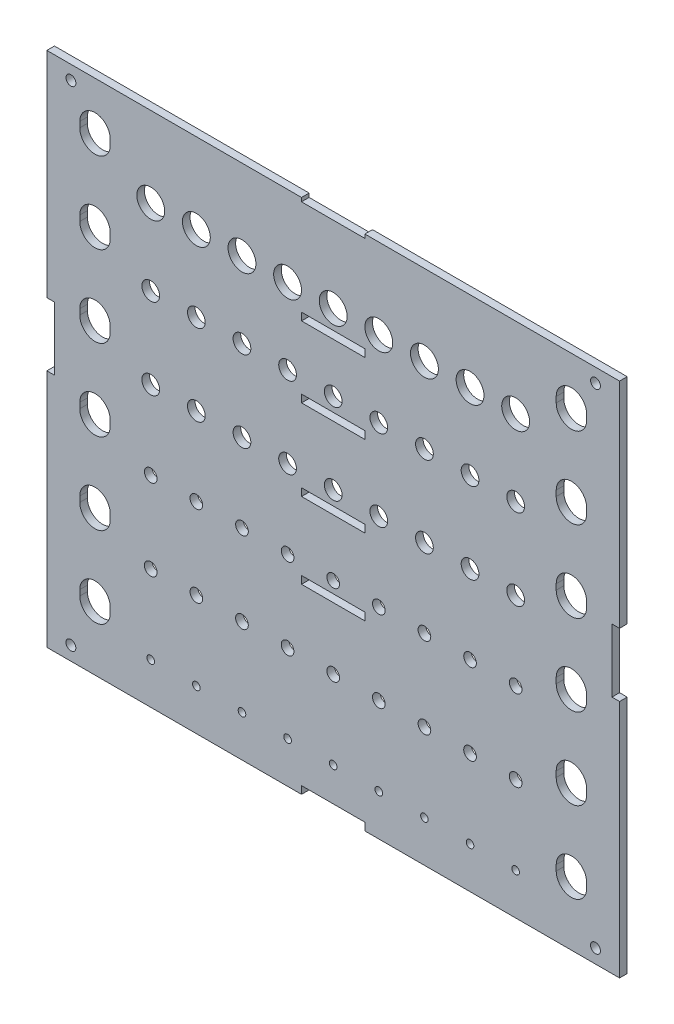
SolidWorks part; units mm, degrees
ref_plane "Спереди" through (0, 0, 0) normal (0, 0, 1) x (1, 0, 0)
ref_plane "Сверху" through (0, 0, 0) normal (0, 1, 0) x (1, 0, 0)
ref_plane "Справа" through (0, 0, 0) normal (1, 0, 0) x (0, 0, -1)
sketch "Эскиз1" plane through (0, 0, 0) normal (0, 0, 1) x (1, 0, 0)
  line L0 (98.0964, 112.1886) -> (98.0964, -117.8114)
  line L1 (-131.9036, 112.1886) -> (98.0964, 112.1886)
  line L2 (-131.9036, 112.1886) -> (-131.9036, -117.8114)
  line L3 (-131.9036, -117.8114) -> (98.0964, -117.8114)
  line L5 (-110.9036, 81.4289) -> (-110.9036, 79.2289) construction
  line L6 (77.0964, 81.4289) -> (77.0964, 79.2289) construction
  line L7 (83.0964, 81.4289) -> (83.0964, 79.2289)
  line L8 (71.0964, 81.4289) -> (71.0964, 79.2289)
  line L9 (-104.9036, 81.4289) -> (-104.9036, 79.2289)
  line L10 (83.0964, 49.4289) -> (83.0964, 47.2289)
  line L11 (71.0964, 49.4289) -> (71.0964, 47.2289)
  line L12 (-110.9036, 49.4289) -> (-110.9036, 47.2289) construction
  line L13 (-104.9036, 49.4289) -> (-104.9036, 47.2289)
  line L14 (-116.9036, 49.4289) -> (-116.9036, 47.2289)
  line L15 (77.0964, 49.4289) -> (77.0964, 47.2289) construction
  line L16 (83.0964, 17.4289) -> (83.0964, 15.2289)
  line L17 (71.0964, 17.4289) -> (71.0964, 15.2289)
  line L18 (-110.9036, 17.4289) -> (-110.9036, 15.2289) construction
  line L19 (-104.9036, 17.4289) -> (-104.9036, 15.2289)
  line L20 (-116.9036, 17.4289) -> (-116.9036, 15.2289)
  line L21 (77.0964, 17.4289) -> (77.0964, 15.2289) construction
  line L22 (83.0964, -14.5711) -> (83.0964, -16.7711)
  line L23 (71.0964, -14.5711) -> (71.0964, -16.7711)
  line L24 (-110.9036, -14.5711) -> (-110.9036, -16.7711) construction
  line L25 (-104.9036, -14.5711) -> (-104.9036, -16.7711)
  line L26 (-116.9036, -14.5711) -> (-116.9036, -16.7711)
  line L27 (77.0964, -14.5711) -> (77.0964, -16.7711) construction
  line L28 (83.0964, -46.5711) -> (83.0964, -48.7711)
  line L29 (71.0964, -46.5711) -> (71.0964, -48.7711)
  line L30 (-110.9036, -46.5711) -> (-110.9036, -48.7711) construction
  line L31 (-104.9036, -46.5711) -> (-104.9036, -48.7711)
  line L32 (-116.9036, 81.4289) -> (-116.9036, 79.2289)
  line L33 (-116.9036, -46.5711) -> (-116.9036, -48.7711)
  line L34 (77.0964, -46.5711) -> (77.0964, -48.7711) construction
  line L35 (83.0964, -78.5711) -> (83.0964, -80.7711)
  line L36 (71.0964, -78.5711) -> (71.0964, -80.7711)
  line L37 (-110.9036, -78.5711) -> (-110.9036, -80.7711) construction
  line L38 (-104.9036, -78.5711) -> (-104.9036, -80.7711)
  line L39 (-116.9036, -78.5711) -> (-116.9036, -80.7711)
  line L40 (77.0964, -78.5711) -> (77.0964, -80.7711) construction
  circle A2 centre (-120.4036, 93.6886) radius 1.95
  circle A3 centre (86.5964, 93.6886) radius 1.95
  circle A4 centre (86.5964, -99.3114) radius 1.95
  circle A5 centre (-120.4036, -99.3114) radius 1.95
  circle A71 centre (-88.9036, 67.4886) radius 5.5
  circle A73 centre (-88.9036, 5.4886) radius 3.5
  circle A75 centre (-88.9036, -57.5114) radius 2.5
  circle A76 centre (-88.9036, -88.5114) radius 1.5
  arc A117 (83.0964, 81.4289) -> (71.0964, 81.4289) centre (77.0964, 81.4289) ccw
  arc A118 (71.0964, 79.2289) -> (83.0964, 79.2289) centre (77.0964, 79.2289) ccw
  arc A119 (71.0964, 47.2289) -> (83.0964, 47.2289) centre (77.0964, 47.2289) ccw
  arc A120 (83.0964, 49.4289) -> (71.0964, 49.4289) centre (77.0964, 49.4289) ccw
  arc A121 (-104.9036, 49.4289) -> (-116.9036, 49.4289) centre (-110.9036, 49.4289) ccw
  arc A122 (-116.9036, 47.2289) -> (-104.9036, 47.2289) centre (-110.9036, 47.2289) ccw
  arc A123 (71.0964, 15.2289) -> (83.0964, 15.2289) centre (77.0964, 15.2289) ccw
  arc A124 (83.0964, 17.4289) -> (71.0964, 17.4289) centre (77.0964, 17.4289) ccw
  arc A125 (-104.9036, 17.4289) -> (-116.9036, 17.4289) centre (-110.9036, 17.4289) ccw
  arc A126 (-116.9036, 15.2289) -> (-104.9036, 15.2289) centre (-110.9036, 15.2289) ccw
  arc A127 (71.0964, -16.7711) -> (83.0964, -16.7711) centre (77.0964, -16.7711) ccw
  arc A128 (83.0964, -14.5711) -> (71.0964, -14.5711) centre (77.0964, -14.5711) ccw
  arc A129 (-104.9036, -14.5711) -> (-116.9036, -14.5711) centre (-110.9036, -14.5711) ccw
  arc A130 (-116.9036, -16.7711) -> (-104.9036, -16.7711) centre (-110.9036, -16.7711) ccw
  arc A131 (71.0964, -48.7711) -> (83.0964, -48.7711) centre (77.0964, -48.7711) ccw
  arc A132 (83.0964, -46.5711) -> (71.0964, -46.5711) centre (77.0964, -46.5711) ccw
  arc A133 (-104.9036, -46.5711) -> (-116.9036, -46.5711) centre (-110.9036, -46.5711) ccw
  arc A134 (-116.9036, -48.7711) -> (-104.9036, -48.7711) centre (-110.9036, -48.7711) ccw
  arc A135 (71.0964, -80.7711) -> (83.0964, -80.7711) centre (77.0964, -80.7711) ccw
  arc A136 (83.0964, -78.5711) -> (71.0964, -78.5711) centre (77.0964, -78.5711) ccw
  arc A137 (-104.9036, -78.5711) -> (-116.9036, -78.5711) centre (-110.9036, -78.5711) ccw
  arc A138 (-116.9036, -80.7711) -> (-104.9036, -80.7711) centre (-110.9036, -80.7711) ccw
  arc A139 (-104.9036, 81.4289) -> (-116.9036, 81.4289) centre (-110.9036, 81.4289) ccw
  arc A140 (-116.9036, 79.2289) -> (-104.9036, 79.2289) centre (-110.9036, 79.2289) ccw
  circle A141 centre (-88.9036, 37.4886) radius 3.5
  circle A142 centre (-88.9036, -25.5114) radius 2.5
  circle A143 centre (-70.9036, 67.4886) radius 5.5
  circle A144 centre (-70.9036, 5.4886) radius 3.5
  circle A145 centre (-70.9036, -57.5114) radius 2.5
  circle A146 centre (-70.9036, -88.5114) radius 1.5
  circle A147 centre (-70.9036, 37.4886) radius 3.5
  circle A148 centre (-70.9036, -25.5114) radius 2.5
  circle A149 centre (-52.9036, 67.4886) radius 5.5
  circle A150 centre (-52.9036, 5.4886) radius 3.5
  circle A151 centre (-52.9036, -57.5114) radius 2.5
  circle A152 centre (-52.9036, -88.5114) radius 1.5
  circle A153 centre (-52.9036, 37.4886) radius 3.5
  circle A154 centre (-52.9036, -25.5114) radius 2.5
  circle A155 centre (-34.9036, 67.4886) radius 5.5
  circle A156 centre (-34.9036, 5.4886) radius 3.5
  circle A157 centre (-34.9036, -57.5114) radius 2.5
  circle A158 centre (-34.9036, -88.5114) radius 1.5
  circle A159 centre (-34.9036, 37.4886) radius 3.5
  circle A160 centre (-34.9036, -25.5114) radius 2.5
  circle A161 centre (-16.9036, 67.4886) radius 5.5
  circle A162 centre (-16.9036, 5.4886) radius 3.5
  circle A163 centre (-16.9036, -57.5114) radius 2.5
  circle A164 centre (-16.9036, -88.5114) radius 1.5
  circle A165 centre (-16.9036, 37.4886) radius 3.5
  circle A166 centre (-16.9036, -25.5114) radius 2.5
  circle A167 centre (1.0964, 67.4886) radius 5.5
  circle A168 centre (1.0964, 5.4886) radius 3.5
  circle A169 centre (1.0964, -57.5114) radius 2.5
  circle A170 centre (1.0964, -88.5114) radius 1.5
  circle A171 centre (1.0964, 37.4886) radius 3.5
  circle A172 centre (1.0964, -25.5114) radius 2.5
  circle A173 centre (19.0964, 67.4886) radius 5.5
  circle A174 centre (19.0964, 5.4886) radius 3.5
  circle A175 centre (19.0964, -57.5114) radius 2.5
  circle A176 centre (19.0964, -88.5114) radius 1.5
  circle A177 centre (19.0964, 37.4886) radius 3.5
  circle A178 centre (19.0964, -25.5114) radius 2.5
  circle A179 centre (37.0964, 67.4886) radius 5.5
  circle A180 centre (37.0964, 5.4886) radius 3.5
  circle A181 centre (37.0964, -57.5114) radius 2.5
  circle A182 centre (37.0964, -88.5114) radius 1.5
  circle A183 centre (37.0964, 37.4886) radius 3.5
  circle A184 centre (37.0964, -25.5114) radius 2.5
  circle A185 centre (55.0964, 67.4886) radius 5.5
  circle A186 centre (55.0964, 5.4886) radius 3.5
  circle A187 centre (55.0964, -57.5114) radius 2.5
  circle A188 centre (55.0964, -88.5114) radius 1.5
  circle A189 centre (55.0964, 37.4886) radius 3.5
  circle A190 centre (55.0964, -25.5114) radius 2.5
  point P7 (-110.9036, 80.3289)
  point P28 (77.0964, 80.3289)
  point P45 (-110.9036, 48.3289)
  point P49 (77.0964, 48.3289)
  point P53 (-110.9036, 79.2289)
  point P60 (-110.9036, 16.3289)
  point P64 (77.0964, 16.3289)
  point P122 (-110.9036, -15.6711)
  point P126 (77.0964, -15.6711)
  point P136 (-110.9036, -47.6711)
  point P140 (77.0964, -47.6711)
  point P150 (-110.9036, -79.6711)
  point P154 (77.0964, -79.6711)
  dimension "D5" = 6
  dimension "D9" = 6
  dimension "D6" = 3.9
  dimension "D7" = 3.9
  dimension "D8" = 3.9
  dimension "D11" = 3.9
  dimension "D1" = 230
  dimension "D2" = 230
  dimension "D4" = 9
  dimension "D10" = 2.2
  dimension "D3" = 2
extrude "Бобышка-Вытянуть1" add sketch "Эскиз1" along normal blind 3
sketch "Эскиз2" plane through (0, 0, 3) normal (0, 0, 1) x (1, 0, 0)
  line L0 (98.0964, -117.8114) -> (98.0964, 112.1886) construction
  line L1 (-131.9036, 112.1886) -> (98.0964, 112.1886)
  line L2 (-131.9036, 112.1886) -> (-131.9036, 99.1886)
  line L3 (-129.9036, 99.1886) -> (96.0964, 99.1886)
  line L4 (98.0964, 112.1886) -> (98.0964, 99.1886)
  line L6 (-131.9036, -117.8114) -> (98.0964, -117.8114)
  line L7 (-131.9036, -117.8114) -> (-131.9036, -104.8114)
  line L8 (-129.9036, -104.8114) -> (96.0964, -104.8114)
  line L9 (98.0964, -117.8114) -> (98.0964, -104.8114)
  line L10 (-131.9036, 112.1886) -> (-124.9036, 112.1886)
  line L11 (-131.9036, 112.1886) -> (-131.9036, -117.8114)
  line L12 (-131.9036, -117.8114) -> (-124.9036, -117.8114)
  line L13 (-129.9036, 99.1886) -> (-129.9036, -104.8114)
  line L14 (98.0964, -117.8114) -> (91.0964, -117.8114)
  line L15 (98.0964, -117.8114) -> (98.0964, 112.1886)
  line L16 (98.0964, 112.1886) -> (91.0964, 112.1886)
  line L17 (96.0964, -104.8114) -> (96.0964, 99.1886)
  line L18 (-29.4036, 59.9886) -> (-4.4036, 59.9886)
  line L19 (-29.4036, 59.9886) -> (-29.4036, 56.9886)
  line L20 (-29.4036, 56.9886) -> (-4.4036, 56.9886)
  line L21 (-4.4036, 59.9886) -> (-4.4036, 56.9886)
  line L22 (-29.4036, 31.9886) -> (-4.4036, 31.9886)
  line L23 (-29.4036, 31.9886) -> (-29.4036, 28.9886)
  line L24 (-29.4036, 28.9886) -> (-4.4036, 28.9886)
  line L25 (-4.4036, 31.9886) -> (-4.4036, 28.9886)
  line L26 (-29.4036, -0.0114) -> (-4.4036, -0.0114)
  line L27 (-29.4036, -0.0114) -> (-29.4036, -3.0114)
  line L28 (-29.4036, -3.0114) -> (-4.4036, -3.0114)
  line L29 (-4.4036, -0.0114) -> (-4.4036, -3.0114)
  line L30 (-29.4036, -30.0114) -> (-4.4036, -30.0114)
  line L31 (-29.4036, -30.0114) -> (-29.4036, -33.0114)
  line L32 (-29.4036, -33.0114) -> (-4.4036, -33.0114)
  line L33 (-4.4036, -30.0114) -> (-4.4036, -33.0114)
  line L34 (-29.4036, -104.8114) -> (-4.4036, -104.8114)
  line L35 (-29.4036, -104.8114) -> (-29.4036, -101.8114)
  line L36 (-29.4036, -101.8114) -> (-4.4036, -101.8114)
  line L37 (-4.4036, -104.8114) -> (-4.4036, -101.8114)
  line L38 (-129.9036, 14.6886) -> (-126.9036, 14.6886)
  line L39 (-129.9036, 14.6886) -> (-129.9036, -10.3114)
  line L40 (-129.9036, -10.3114) -> (-126.9036, -10.3114)
  line L41 (-126.9036, 14.6886) -> (-126.9036, -10.3114)
  line L42 (96.0964, 14.6886) -> (93.0964, 14.6886)
  line L43 (96.0964, 14.6886) -> (96.0964, -10.3114)
  line L44 (96.0964, -10.3114) -> (93.0964, -10.3114)
  line L45 (93.0964, 14.6886) -> (93.0964, -10.3114)
  line L46 (-29.4036, 99.1886) -> (-4.4036, 99.1886)
  line L47 (-29.4036, 99.1886) -> (-29.4036, 97.6886)
  line L48 (-29.4036, 97.6886) -> (-4.4036, 97.6886)
  line L49 (-4.4036, 99.1886) -> (-4.4036, 97.6886)
  circle A0 centre (-16.9036, 67.4886) radius 5.5 construction
  circle A2 centre (-16.9036, 37.4886) radius 3.5 construction
  circle A5 centre (-16.9036, 5.4886) radius 3.5 construction
  circle A7 centre (-16.9036, -25.5114) radius 2.5 construction
  dimension "D7" = 2
  dimension "D1" = 13
  dimension "D2" = 2
  dimension "D3" = 2
  dimension "D4" = 13
  dimension "D5" = 3
  dimension "D6" = 25
  dimension "D8" = 3
  dimension "D9" = 3
  dimension "D10" = 3
  dimension "D11" = 25
  dimension "D12" = 25
  dimension "D13" = 25
  dimension "D14" = 2
  dimension "D15" = 2
  dimension "D16" = 2
  dimension "D17" = 25
  dimension "D18" = 1.5
  dimension "D19" = 226
  dimension "D20" = 3
  dimension "D21" = 3
  dimension "D22" = 25
  dimension "D23" = 25
  dimension "D24" = 3
  dimension "D25" = 25
  dimension "D26" = 100.5
  dimension "D27" = 100.5
  dimension "D28" = 84.5
  dimension "D29" = 84.5
  dimension "D30" = 100.5
  dimension "D31" = 39.2
  dimension "D32" = 67.2
  dimension "D33" = 100.5
  dimension "D34" = 100.5
  dimension "D35" = 99.2
  dimension "D36" = 129.2
  dimension "D37" = 100.5
extrude "Вырез-Вытянуть1" cut sketch "Эскиз2" against normal blind 10 contours L9 L15 L4 L1 L2 L11 L7 L6 L17 L8 L13 L3 | L21 L18 L19 L20 | L29 L26 L27 L28 | L41 L38 L13 L40 | L48 L49 L46 L47 | L22 L25 L24 L23 | L30 L33 L32 L31 | L45 L44 L43 L42 | L36 L37 L34 L35
